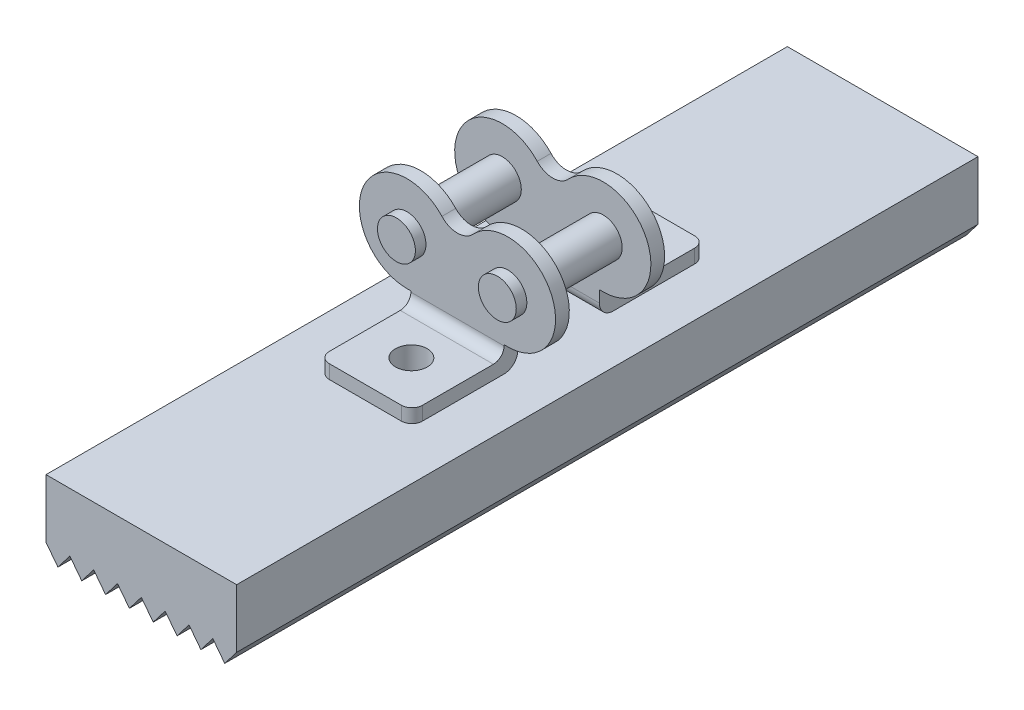
SolidWorks part; units mm, degrees
ref_plane "Alzado" through (0, 0, 0) normal (0, 0, 1) x (1, 0, 0)
ref_plane "Planta" through (0, 0, 0) normal (0, 1, 0) x (1, 0, 0)
ref_plane "Vista lateral" through (0, 0, 0) normal (1, 0, 0) x (0, 0, -1)
sketch "Sketch1" plane through (0, 0, 0) normal (0, 0, 1) x (1, 0, 0)
  line L0 (-9.2625, 0) -> (9.2625, 0) construction
  line L1 (0, 10.9987) -> (0, -12.9647) construction
  line L2 (-4.7625, -4.5) -> (4.7625, -4.5)
  arc A0 (-1.4654, 3.0625) -> (-4.7625, -4.5) centre (-4.7625, 0) ccw
  arc A1 (-1.4654, 3.0625) -> (1.4654, 3.0625) centre (0, 4.4236) ccw
  arc A2 (1.4654, 3.0625) -> (4.7625, -4.5) centre (4.7625, 0) cw
  point P4 (0, 0)
  point P15 (0, -4.5)
  dimension "D1" = 9
  dimension "D3" = 2
  dimension "D2" = 9.525
extrude "Boss-Extrude1" add sketch "Sketch1" along normal blind 1.3
sketch "Sketch2" plane through (0, 0, 1.3) normal (0, 0, 1) x (1, 0, 0)
  circle A0 centre (-4.7625, 0) radius 1.79
  circle A1 centre (4.7625, 0) radius 1.79
  dimension "D1" = 3.58
extrude "Boss-Extrude2" add sketch "Sketch2" against normal blind 2.3 and the other way blind 10
ref_plane "Plane1" through (0, 0, 5.15) normal (0, 0, -1) x (-1, 0, 0)
sketch "Sketch4" plane through (0, -4.5, 0) normal (0, -1, 0) x (1, 0, 0)
  line L0 (-4.7625, 1.3) -> (4.7625, 1.3) construction
  line L1 (-4.4, 1.3) -> (4.4, 1.3)
  line L2 (-4.4, 1.3) -> (-4.4, 0)
  line L3 (-4.4, 0) -> (4.4, 0)
  line L4 (4.4, 1.3) -> (4.4, 0)
  line L5 (2.9725, 0) -> (6.5525, 0) construction
  point P8 (0, 1.3)
  dimension "D1" = 8.8
extrude "Boss-Extrude4" add sketch "Sketch4" along normal blind 2.4
sketch "Sketch3" plane through (0, -6.9, 0) normal (0, -1, 0) x (1, 0, 0)
  line L0 (-4.7625, 1.3) -> (-4.4, 1.3) construction
  line L1 (-4.4, 1.3) -> (4.4, 1.3)
  line L2 (-4.4, 1.3) -> (-4.4, -8.7)
  line L3 (-4.4, -8.7) -> (4.4, -8.7)
  line L4 (4.4, 1.3) -> (4.4, -8.7)
  point P6 (0, 1.3)
  dimension "D1" = 8.8
  dimension "D2" = 10
extrude "Boss-Extrude3" add sketch "Sketch3" against normal blind 1.3
fillet "Fillet4" radius 1.3 1 edges at (0, -6.9, 1.3)
fillet "Fillet6" radius 1 1 edges at (0, -5.6, 0)
sketch "Sketch5" plane through (0, -6.9, 0) normal (0, -1, 0) x (1, 0, 0)
  line L0 (-4.4, 0) -> (4.4, -8.7) construction
  line L1 (-4.4, -8.7) -> (4.4, 0) construction
  circle A0 centre (0, -4.35) radius 1.5
  dimension "D1" = 3
extrude "Cut-Extrude1" cut sketch "Sketch5" against normal blind 2.4
fillet "Fillet7" radius 1 2 edges at (4.4, -6.25, -8.7) (-4.4, -6.25, -8.7)
mirror "Mirror1" about plane through (0, 0, 5.15) normal (0, 0, -1) of "Fillet7", "Cut-Extrude1", "Fillet6", "Fillet4", "Boss-Extrude4", "Boss-Extrude1", "Boss-Extrude3"
sketch "Sketch6" plane through (0, -6.9, 0) normal (0, -1, 0) x (1, 0, 0)
  line L0 (0, 19) -> (0, -8.7) construction
  line L1 (-3.4, 19) -> (3.4, 19) construction
  line L2 (-3.4, -8.7) -> (3.4, -8.7) construction
  line L4 (-9, 40.15) -> (9, 40.15)
  line L5 (-9, 40.15) -> (-9, -29.85)
  line L6 (-9, -29.85) -> (9, -29.85)
  line L7 (9, 40.15) -> (9, -29.85)
  line L8 (-9, 40.15) -> (9, -29.85) construction
  line L9 (-9, -29.85) -> (9, 40.15) construction
  circle A0 centre (0, 14.65) radius 1.5 construction
  circle A1 centre (0, -4.35) radius 1.5 construction
  circle A2 centre (0, 14.65) radius 1.5
  circle A3 centre (0, -4.35) radius 1.5
  point P12 (0, 5.15)
  dimension "D1" = 18
  dimension "D2" = 70
extrude "Boss-Extrude5" add sketch "Sketch6" along normal blind 7
sketch "Sketch9" plane through (0, -13.9, 0) normal (0, -1, 0) x (1, 0, 0)
  circle A0 centre (0, 14.65) radius 4
  circle A1 centre (0, -4.35) radius 4
  dimension "D1" = 8
extrude "Cut-Extrude3" cut sketch "Sketch9" against normal blind 3
sketch "Sketch11" plane through (0, 0, 40.15) normal (0, 0, 1) x (1, 0, 0)
  line L1 (-9, -13.9) -> (-9, -6.9) construction
  line L2 (9, -13.9) -> (9, -6.9) construction
  line L3 (9, -13.9) -> (-9, -13.9) construction
  line L4 (9, -12.433) -> (7.875, -13.9)
  line L5 (7.875, -13.9) -> (6.75, -12.433)
  line L6 (5.625, -13.9) -> (4.5, -12.433)
  line L7 (6.75, -12.433) -> (5.625, -13.9)
  line L8 (3.375, -13.9) -> (2.25, -12.433)
  line L9 (4.5, -12.433) -> (3.375, -13.9)
  line L10 (1.125, -13.9) -> (0, -12.433)
  line L11 (2.25, -12.433) -> (1.125, -13.9)
  line L12 (-1.125, -13.9) -> (-2.25, -12.433)
  line L13 (0, -12.433) -> (-1.125, -13.9)
  line L14 (-3.375, -13.9) -> (-4.5, -12.433)
  line L15 (-2.25, -12.433) -> (-3.375, -13.9)
  line L16 (-5.625, -13.9) -> (-6.75, -12.433)
  line L17 (-4.5, -12.433) -> (-5.625, -13.9)
  line L18 (-7.875, -13.9) -> (-9, -12.433)
  line L19 (-6.75, -12.433) -> (-7.875, -13.9)
  line L22 (-9, -12.433) -> (-9, -14.9)
  line L23 (-9, -14.9) -> (9, -14.9)
  line L24 (9, -12.433) -> (9, -14.9)
  dimension "D1" = 1
  dimension "D2" = 2.25
  dimension "D3" = 1.125
  dimension "D4" = 8
extrude "Cut-Extrude4" cut sketch "Sketch11" against normal through all
